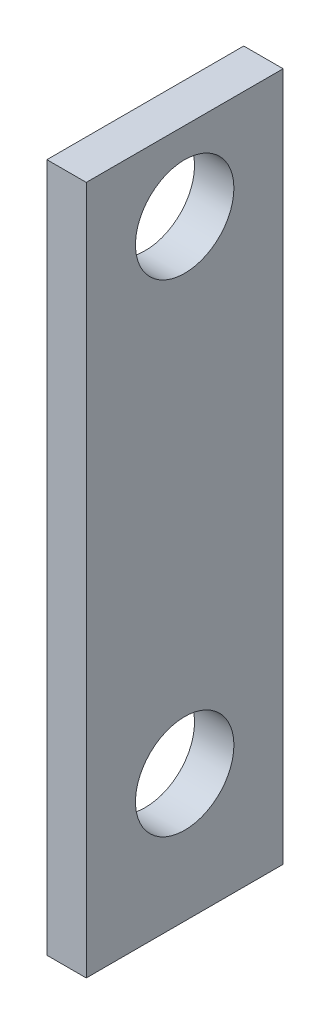
SolidWorks part; units mm, degrees
ref_plane "Front Plane" through (0, 0, 0) normal (0, 0, 1) x (1, 0, 0)
ref_plane "Top Plane" through (0, 0, 0) normal (0, 1, 0) x (1, 0, 0)
ref_plane "Right Plane" through (0, 0, 0) normal (1, 0, 0) x (0, 0, -1)
sketch "Sketch2" plane through (0, 0, 0) normal (1, 0, 0) x (0, 0, -1)
  line L0 (0, 17.5) -> (0, -17.5) construction
  line L1 (5, -17.5) -> (-5, -17.5)
  line L2 (5, -17.5) -> (5, 17.5)
  line L3 (5, 17.5) -> (-5, 17.5)
  line L4 (-5, -17.5) -> (-5, 17.5)
  line L5 (5, -17.5) -> (-5, 17.5) construction
  line L6 (5, 17.5) -> (-5, -17.5) construction
  point P0 (0, 0)
  dimension "D1" = 35
  dimension "D2" = 10
extrude "Boss-Extrude1" add sketch "Sketch2" along normal blind 2
sketch "Sketch3" plane through (2, 0, 0) normal (1, 0, 0) x (0, 0, -1)
  line L0 (0, 0) -> (0, 17.5) construction
  line L1 (5, 17.5) -> (-5, 17.5) construction
  line L2 (0, 0) -> (0, -17.5) construction
  line L9 (-5, -17.5) -> (5, -17.5) construction
  circle A0 centre (0, -11) radius 2.5
  circle A1 centre (0, 13.5) radius 2.5
  dimension "D4" = 5
  dimension "D5" = 11
  dimension "D1" = 5
  dimension "D2" = 4
extrude "Cut-Extrude1" cut sketch "Sketch3" against normal blind 2
